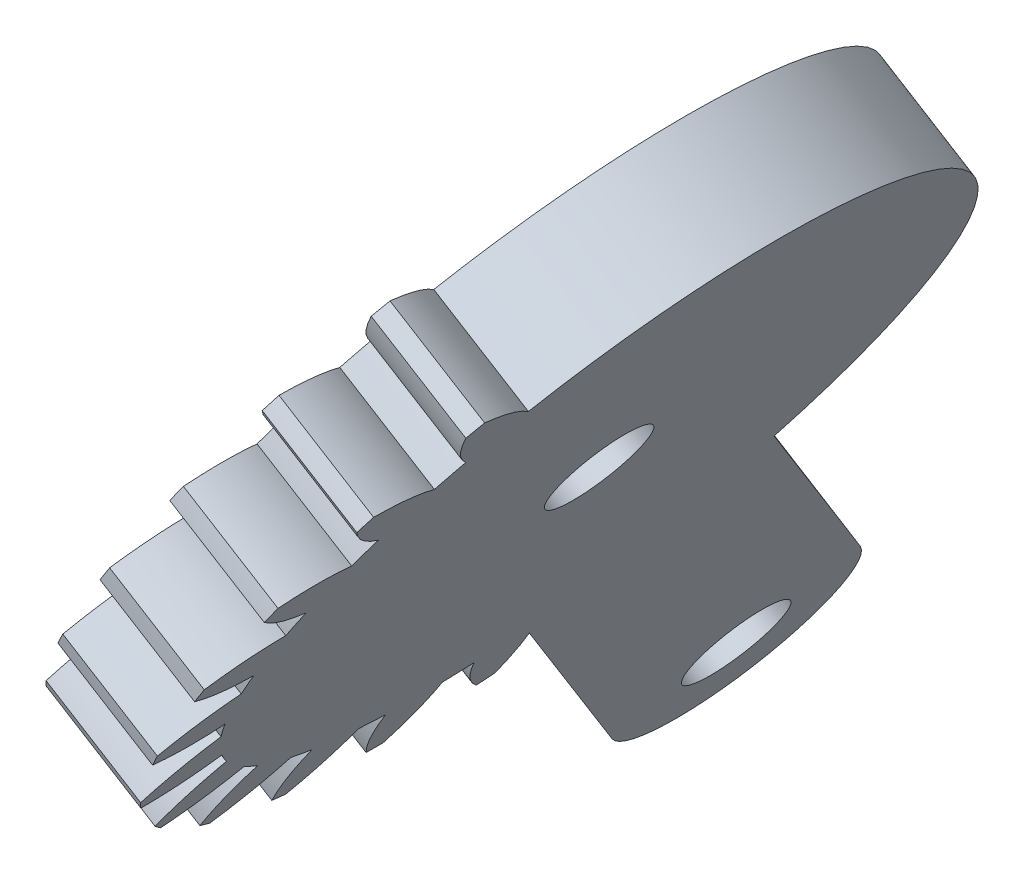
SolidWorks part; units mm, degrees
ref_plane "Front Plane" through (0, 0, 0) normal (0, 0, 1) x (1, 0, 0)
ref_plane "Top Plane" through (0, 0, 0) normal (0, 1, 0) x (1, 0, 0)
ref_plane "Right Plane" through (0, 0, 0) normal (1, 0, 0) x (0, 0, -1)
ref_plane "Plane1" through (-201.8493, 125.418, 0.5938) normal (0.8494, -0.5278, -0.0025) x (0.5278, 0.8494, 0)
sketch "Sketch1" plane through (-201.8493, 125.418, 0.5938) normal (0.8494, -0.5278, -0.0025) x (0.5278, 0.8494, 0)
  line L0 (130.9451, 58.8098) -> (146.5798, 70.1901)
  line L1 (141.2445, 76.2015) -> (126.2371, 65.2779)
  circle A0 centre (153.4525, 80.14) radius 1.75
  circle A1 centre (128.5911, 62.0439) radius 1.75
  arc A2 (146.5798, 70.1901) -> (162.9003, 87.6882) centre (153.4525, 80.14) ccw
  arc A3 (162.9003, 87.6882) -> (164.2649, 89.988) centre (159.0832, 91.5078) ccw
  arc A4 (164.2649, 89.988) -> (163.8349, 90.4404) centre (153.4525, 80.14) ccw
  arc A5 (163.8349, 90.4404) -> (161.4689, 89.1939) centre (165.0906, 85.1884) ccw
  arc A6 (161.4689, 89.1939) -> (160.6248, 89.8762) centre (153.4525, 80.14) ccw
  arc A7 (160.6248, 89.8762) -> (161.3476, 92.4509) centre (155.9491, 92.5778) ccw
  arc A8 (161.3476, 92.4509) -> (160.8152, 92.7766) centre (153.4525, 80.14) ccw
  arc A9 (160.8152, 92.7766) -> (158.8525, 90.9602) centre (163.3874, 88.0286) ccw
  arc A10 (158.8525, 90.9602) -> (157.8605, 91.4008) centre (153.4525, 80.14) ccw
  arc A11 (157.8605, 91.4008) -> (157.8923, 94.0748) centre (152.6449, 92.8002) ccw
  arc A12 (157.8923, 94.0748) -> (157.2937, 94.2516) centre (153.4525, 80.14) ccw
  arc A13 (157.2937, 94.2516) -> (155.868, 91.9891) centre (161.0072, 90.3311) ccw
  arc A14 (155.868, 91.9891) -> (154.7958, 92.158) centre (153.4525, 80.14) ccw
  arc A15 (154.7958, 92.158) -> (154.1345, 94.7491) centre (149.3958, 92.1598) ccw
  arc A16 (154.1345, 94.7491) -> (153.5105, 94.7649) centre (153.4525, 80.14) ccw
  arc A17 (153.5105, 94.7649) -> (152.7189, 92.2105) centre (158.1121, 91.9391) ccw
  arc A18 (152.7189, 92.2105) -> (151.6395, 92.0961) centre (153.4525, 80.14) ccw
  arc A19 (151.6395, 92.0961) -> (150.3301, 94.4278) centre (146.4231, 90.7002) ccw
  arc A20 (150.3301, 94.4278) -> (149.7233, 94.2816) centre (153.4525, 80.14) ccw
  arc A21 (149.7233, 94.2816) -> (149.6199, 91.6094) centre (154.8995, 92.7431) ccw
  arc A22 (149.6199, 91.6094) -> (148.6068, 91.2195) centre (153.4525, 80.14) ccw
  arc A23 (148.6068, 91.2195) -> (146.7385, 93.1328) centre (143.9294, 88.521) ccw
  arc A24 (146.7385, 93.1328) -> (146.1903, 92.8345) centre (153.4525, 80.14) ccw
  arc A25 (146.1903, 92.8345) -> (146.782, 90.2266) centre (151.5883, 92.6882) ccw
  arc A26 (146.782, 90.2266) -> (145.9044, 89.5878) centre (153.4525, 80.14) ccw
  arc A27 (145.9044, 89.5878) -> (143.6045, 90.9524) centre (142.0847, 85.7707) ccw
  arc A28 (143.6045, 90.9524) -> (143.1521, 90.5224) centre (153.4525, 80.14) ccw
  arc A29 (143.1521, 90.5224) -> (144.3987, 88.1564) centre (148.4041, 91.7781) ccw
  arc A30 (144.3987, 88.1564) -> (143.7163, 87.3123) centre (153.4525, 80.14) ccw
  arc A31 (143.7163, 87.3123) -> (141.1416, 88.0352) centre (141.0148, 82.6366) ccw
  arc A32 (141.1416, 88.0352) -> (140.816, 87.5027) centre (153.4525, 80.14) ccw
  arc A33 (140.816, 87.5027) -> (142.6324, 85.54) centre (145.564, 90.0749) ccw
  arc A34 (142.6324, 85.54) -> (142.1918, 84.548) centre (153.4525, 80.14) ccw
  arc A35 (142.1918, 84.548) -> (139.5177, 84.5798) centre (140.7924, 79.3324) ccw
  arc A36 (139.5177, 84.5798) -> (139.341, 83.9812) centre (153.4525, 80.14) ccw
  arc A37 (139.341, 83.9812) -> (141.6035, 82.5555) centre (143.2614, 87.6947) ccw
  arc A38 (141.6035, 82.5555) -> (141.4346, 81.4833) centre (153.4525, 80.14) ccw
  arc A39 (141.4346, 81.4833) -> (138.8434, 80.822) centre (141.4328, 76.0833) ccw
  arc A40 (138.8434, 80.822) -> (138.8276, 80.198) centre (153.4525, 80.14) ccw
  arc A41 (138.8276, 80.198) -> (141.382, 79.4064) centre (141.6534, 84.7996) ccw
  arc A42 (141.382, 79.4064) -> (141.4964, 78.3271) centre (153.4525, 80.14) ccw
  arc A43 (141.4964, 78.3271) -> (139.1647, 77.0176) centre (142.8923, 73.1106) ccw
  arc A44 (139.1647, 77.0176) -> (139.311, 76.4108) centre (153.4525, 80.14) ccw
  arc A45 (139.311, 76.4108) -> (141.2445, 76.2015) centre (140.8495, 81.587) ccw
  arc A46 (126.2371, 65.2779) -> (130.9451, 58.8098) centre (128.5911, 62.0439) ccw
extrude "Boss-Extrude1" add sketch "Sketch1" against normal blind 4
